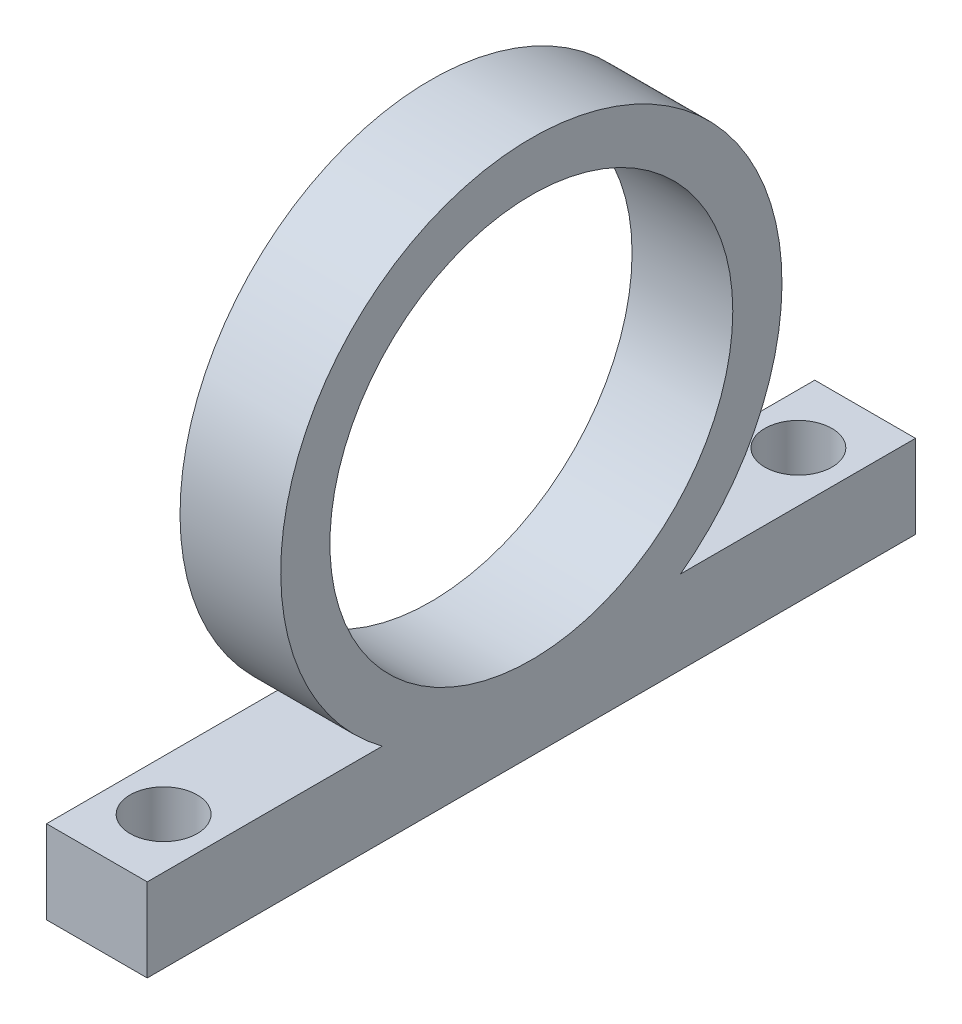
SolidWorks part; units mm, degrees
ref_plane "Front Plane" through (0, 0, 0) normal (0, 0, 1) x (1, 0, 0)
ref_plane "Top Plane" through (0, 0, 0) normal (0, 1, 0) x (1, 0, 0)
ref_plane "Right Plane" through (0, 0, 0) normal (1, 0, 0) x (0, 0, -1)
sketch "Sketch1" plane through (0, 0, 0) normal (1, 0, 0) x (0, 0, -1)
  line L0 (44.4142, -60) -> (114.4142, -60)
  line L1 (-44.4142, -60) -> (-114.4142, -60)
  line L3 (-114.4142, -60) -> (-114.4142, -84.8)
  line L4 (-114.4142, -84.8) -> (138.0665, -84.8)
  line L5 (114.4142, -60) -> (114.4142, -84.8)
  circle A0 centre (0, 0) radius 60
  arc A1 (44.4142, -60) -> (-44.4142, -60) centre (0, 0) ccw
  dimension "D1" = 120
  dimension "D2" = 149.3
  dimension "D4" = 24.8
extrude "Boss-Extrude1" add sketch "Sketch1" along normal blind 30 contours L0 A1 L1 L3 L4 L5 A0
sketch "Sketch2" plane through (0, -60, 0) normal (0, 1, 0) x (1, 0, 0)
  line L0 (0, -94.5321) -> (36.148, -94.5321) construction
  line L1 (0, -74.65) -> (30, -74.65) construction
  line L2 (0, 0) -> (43.1114, 0) construction
  line L4 (0, -114.4142) -> (0, -74.65)
  circle A0 centre (15, -94.5321) radius 10
  circle A1 centre (15, 94.5321) radius 10
  dimension "D1" = 20
extrude "Cut-Extrude1" cut sketch "Sketch2" against normal through all contours A0 | A1
